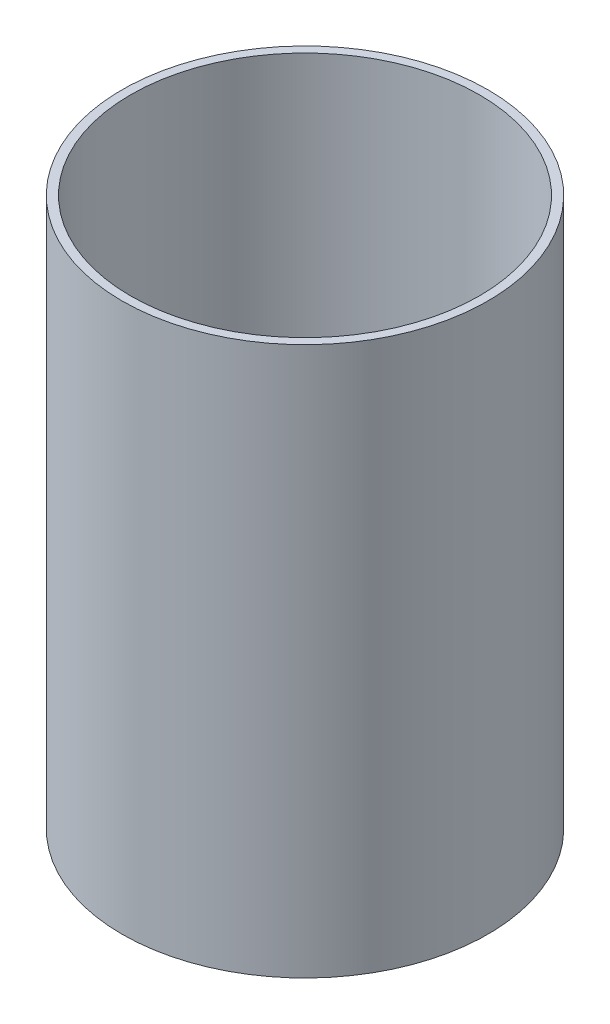
SolidWorks part; units mm, degrees
material "E-Glass Fiber"
ref_plane "Front Plane" through (0, 0, 0) normal (0, 0, 1) x (1, 0, 0)
ref_plane "Top Plane" through (0, 0, 0) normal (0, 1, 0) x (1, 0, 0)
ref_plane "Right Plane" through (0, 0, 0) normal (1, 0, 0) x (0, 0, -1)
sketch "Sketch1" plane through (0, 0, 0) normal (0, 1, 0) x (1, 0, 0)
  circle A0 centre (0, 0) radius 81
  circle A1 centre (0, 0) radius 85
  dimension "D1" = 162
  dimension "D2" = 170
extrude "Boss-Extrude1" add sketch "Sketch1" along normal blind 254.85
